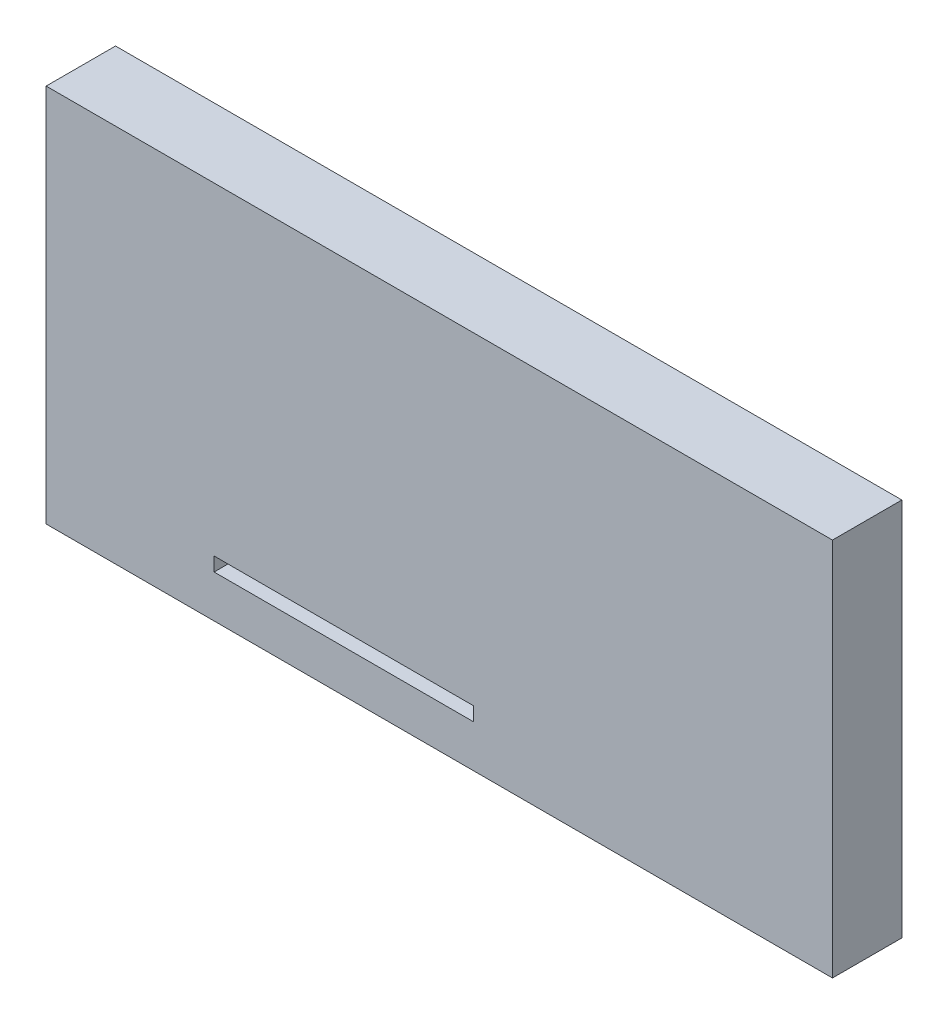
SolidWorks part; units mm, degrees
ref_plane "Front Plane" through (0, 0, 0) normal (0, 0, 1) x (1, 0, 0)
ref_plane "Top Plane" through (0, 0, 0) normal (0, 1, 0) x (1, 0, 0)
ref_plane "Right Plane" through (0, 0, 0) normal (1, 0, 0) x (0, 0, -1)
sketch "Sketch2" plane through (0, 0, 0) normal (0, 0, 1) x (1, 0, 0)
  line L1 (-85, -41) -> (85, -41)
  line L2 (-85, -41) -> (-85, 41)
  line L3 (-85, 41) -> (85, 41)
  line L4 (85, -41) -> (85, 41)
  line L5 (-85, -41) -> (85, 41) construction
  line L6 (-85, 41) -> (85, -41) construction
  point P0 (0, 0)
  dimension "D1" = 170
  dimension "D2" = 82
extrude "Boss-Extrude1" add sketch "Sketch2" along normal blind 15
ref_plane "Plane1" through (0, 0, 0) normal (1, 0, 0) x (0, 0, -1)
sketch "Sketch5" plane through (0, 0, 0) normal (1, 0, 0) x (0, 0, -1)
  line L0 (0, 29.1639) -> (5.5, 29.1639)
  line L1 (0, -41) -> (0, 41) construction
  line L2 (13.5, 21.1639) -> (13.5, -15.8361)
  arc A0 (13.5, 21.1639) -> (5.5, 29.1639) centre (5.5, 21.1639) ccw
  point P7 (13.5, 29.1639)
  dimension "D3" = 8
  dimension "D1" = 13.5
  dimension "D2" = 45
sketch "Sketch6" plane through (0, 0, 0) normal (0, 0, -1) x (-1, 0, 0)
  circle A0 centre (0, 29.1639) radius 2
sweep "Sweep1" add profiles "Sketch6" path "Sketch5"
sketch "Sketch7" plane through (0, 0, 0) normal (0, 0, -1) x (-1, 0, 0)
  line L1 (-7.3752, -28.8307) -> (48.6869, -28.8307)
  line L2 (-7.3752, -28.8307) -> (-7.3752, -31.8307)
  line L3 (-7.3752, -31.8307) -> (48.6869, -31.8307)
  line L4 (48.6869, -28.8307) -> (48.6869, -31.8307)
  dimension "D1" = 3
extrude "Cut-Extrude2" cut sketch "Sketch7" against normal through all
pattern_linear "LPattern1" count 2 spacing 10 along (-1, 0, 0) of "Sweep1"
